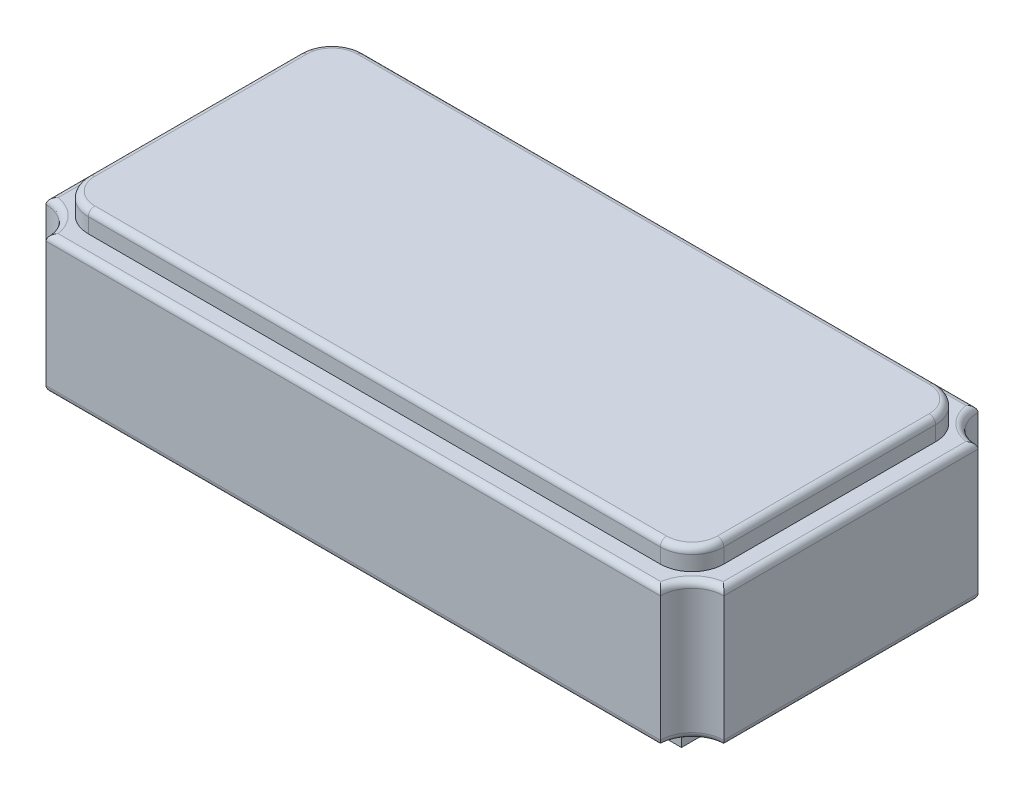
SolidWorks part; units mm, degrees
ref_plane "Спереди" through (0, 0, 0) normal (0, 0, 1) x (1, 0, 0)
ref_plane "Сверху" through (0, 0, 0) normal (0, 1, 0) x (1, 0, 0)
ref_plane "Справа" through (0, 0, 0) normal (1, 0, 0) x (0, 0, -1)
sketch "Эскиз1" plane through (0, 0, 0) normal (0, 1, 0) x (1, 0, 0)
  line L0 (-1.45, 0.75) -> (1.45, 0.75)
  line L1 (-1.6, -0.75) -> (1.6, -0.75) construction
  line L2 (-1.6, -0.75) -> (-1.6, 0.75) construction
  line L3 (-1.6, 0.75) -> (1.6, 0.75) construction
  line L4 (1.6, -0.75) -> (1.6, 0.75) construction
  line L5 (-1.6, -0.75) -> (1.6, 0.75) construction
  line L6 (-1.6, 0.75) -> (1.6, -0.75) construction
  line L7 (-1.6, 0.6) -> (-1.6, -0.6)
  line L8 (-1.45, -0.75) -> (1.45, -0.75)
  line L9 (1.6, -0.6) -> (1.6, 0.6)
  arc A0 (-1.6, 0.6) -> (-1.45, 0.75) centre (-1.6, 0.75) ccw
  arc A1 (-1.45, -0.75) -> (-1.6, -0.6) centre (-1.6, -0.75) ccw
  arc A2 (1.6, -0.6) -> (1.45, -0.75) centre (1.6, -0.75) ccw
  arc A3 (1.45, 0.75) -> (1.6, 0.6) centre (1.6, 0.75) ccw
  point P0 (0, 0)
  point P14 (0, 0)
  point P15 (0, 0)
  point P16 (0, 0)
  dimension "D3" = 0.15
  dimension "D1" = 3.2
  dimension "D2" = 1.5
extrude "Бобышка-Вытянуть1" add sketch "Эскиз1" along normal blind 0.65 from offset 0.05
sketch "Эскиз2" plane through (0, 0.7, 0) normal (0, 1, 0) x (1, 0, 0)
  line L1 (-1.35, -0.65) -> (1.35, -0.65)
  line L2 (-1.5, -0.5) -> (-1.5, 0.5)
  line L3 (-1.35, 0.65) -> (1.35, 0.65)
  line L4 (1.5, -0.5) -> (1.5, 0.5)
  line L5 (-1.5, -0.65) -> (1.5, 0.65) construction
  line L6 (-1.5, 0.65) -> (1.5, -0.65) construction
  arc A0 (1.35, 0.65) -> (1.5, 0.5) centre (1.35, 0.5) cw
  arc A1 (1.35, -0.65) -> (1.5, -0.5) centre (1.35, -0.5) ccw
  arc A2 (-1.35, -0.65) -> (-1.5, -0.5) centre (-1.35, -0.5) cw
  arc A3 (-1.5, 0.5) -> (-1.35, 0.65) centre (-1.35, 0.5) cw
  point P0 (0, 0)
  dimension "D1" = 0.15
extrude "Бобышка-Вытянуть2" add sketch "Эскиз2" along normal blind 0.1 separate body
fillet "Скругление1" radius 0.03 8 edges at (-1.4939, 0.7, -0.6439) (0, 0.7, -0.75) (1.4939, 0.7, -0.6439) (1.6, 0.7, 0) (1.4939, 0.7, 0.6439) (-1.6, 0.7, 0) (-1.4939, 0.7, 0.6439) (0, 0.7, 0.75)
fillet "Скругление2" radius 0.03 8 edges at (1.4939, 0.05, 0.6439) (1.6, 0.05, 0) (1.4939, 0.05, -0.6439) (0, 0.05, -0.75) (-1.4939, 0.05, -0.6439) (-1.6, 0.05, 0) (-1.4939, 0.05, 0.6439) (0, 0.05, 0.75)
fillet "Скругление3" radius 0.03 8 edges at (1.5, 0.8, 0) (1.4561, 0.8, 0.6061) (0, 0.8, 0.65) (-1.4561, 0.8, 0.6061) (-1.5, 0.8, 0) (-1.4561, 0.8, -0.6061) (0, 0.8, -0.65) (1.4561, 0.8, -0.6061)
sketch "Эскиз3" plane through (0, 0, 0) normal (0, 1, 0) x (1, 0, 0)
  line L0 (0, 0.9244) -> (0, -0.8696) construction
  line L1 (-1.45, -0.65) -> (-0.75, -0.65)
  line L2 (-1.45, -0.65) -> (-1.45, 0.65)
  line L3 (-1.45, 0.65) -> (-1.15, 0.65)
  line L4 (-0.75, -0.65) -> (-0.75, 0.25)
  line L5 (-1.45, -0.65) -> (-0.75, 0.65) construction
  line L6 (-1.45, 0.65) -> (-0.75, -0.65) construction
  line L7 (0.75, -0.65) -> (0.75, 0.65)
  line L8 (1.45, 0.65) -> (0.75, 0.65)
  line L9 (1.45, -0.65) -> (1.45, 0.65)
  line L10 (1.45, -0.65) -> (0.75, -0.65)
  line L11 (-1.15, 0.65) -> (-0.75, 0.25)
  point P0 (-1.1, 0)
  point P8 (0, 0)
  point P9 (0, 0)
extrude "Бобышка-Вытянуть3" add sketch "Эскиз3" along normal blind 0.05 separate body
